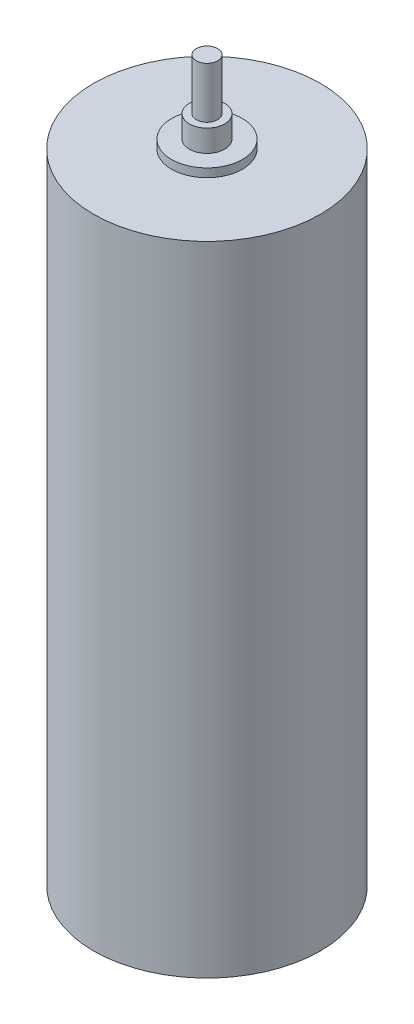
SolidWorks part; units mm, degrees
ref_plane "Front Plane" through (0, 0, 0) normal (0, 0, 1) x (1, 0, 0)
ref_plane "Top Plane" through (0, 0, 0) normal (0, 1, 0) x (1, 0, 0)
ref_plane "Right Plane" through (0, 0, 0) normal (1, 0, 0) x (0, 0, -1)
sketch "Sketch1" plane through (0, 0, 0) normal (0, 1, 0) x (1, 0, 0)
  circle A0 centre (0, 0) radius 8
  dimension "D1" = 16
extrude "Boss-Extrude1" add sketch "Sketch1" against normal blind 45
sketch "Sketch2" plane through (0, 0, 0) normal (0, 1, 0) x (1, 0, 0)
  circle A0 centre (0, 0) radius 2.5
  dimension "D1" = 5
extrude "Boss-Extrude2" add sketch "Sketch2" along normal blind 0.6
sketch "Sketch3" plane through (0, 0, 0) normal (0, 1, 0) x (1, 0, 0)
  circle A0 centre (0, 0) radius 0.75
  dimension "D1" = 1.5
extrude "Boss-Extrude3" add sketch "Sketch3" along normal blind 5.75
sketch "Sketch5" plane through (0, 0, 0) normal (0, 1, 0) x (1, 0, 0)
  circle A0 centre (0, 0) radius 1.25
  dimension "D1" = 2.5
extrude "Boss-Extrude4" add sketch "Sketch5" along normal blind 2.15
